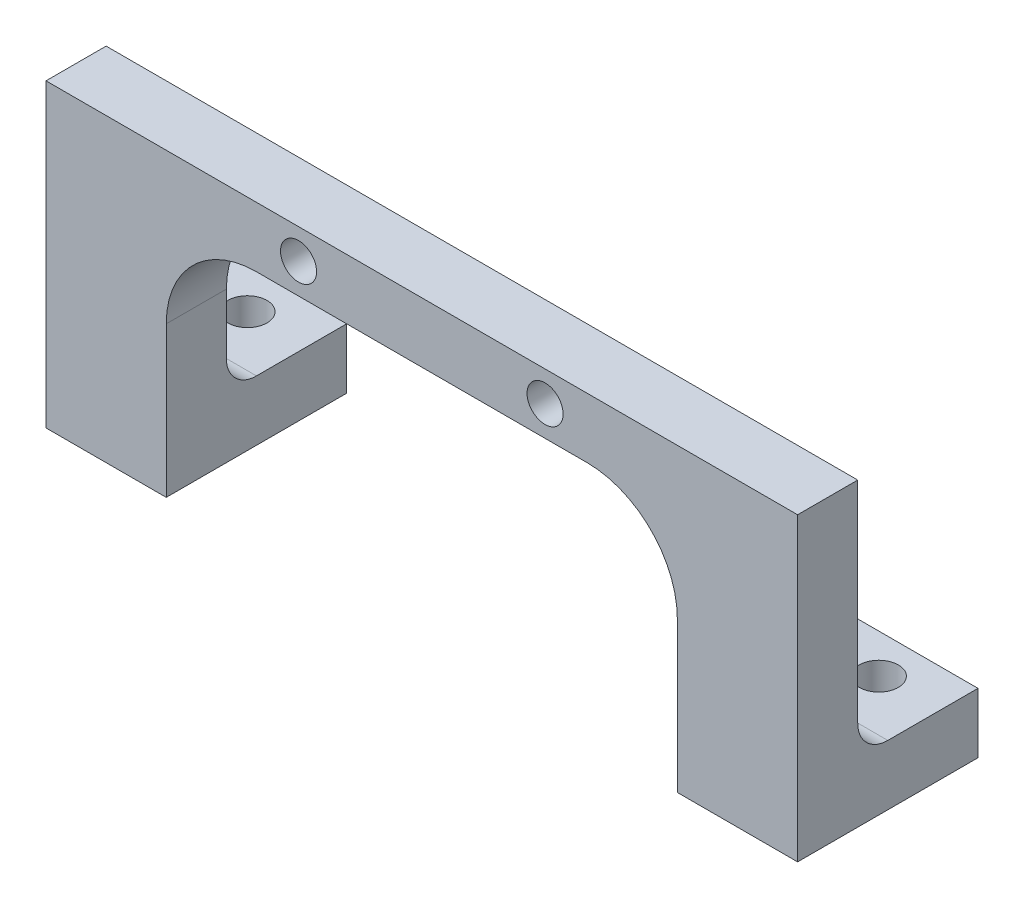
SolidWorks part; units mm, degrees
ref_plane "Front Plane" through (0, 0, 0) normal (0, 0, 1) x (1, 0, 0)
ref_plane "Top Plane" through (0, 0, 0) normal (0, 1, 0) x (1, 0, 0)
ref_plane "Right Plane" through (0, 0, 0) normal (1, 0, 0) x (0, 0, -1)
sketch "Sketch1" plane through (0, 0, 0) normal (1, 0, 0) x (0, 0, -1)
  line L1 (-0.3503, 12.7) -> (4.7297, 12.7)
  line L2 (-0.3503, 12.7) -> (-0.3503, -12.7)
  line L4 (4.7297, 12.7) -> (4.7297, -5.08)
  line L5 (-0.3503, 12.7) -> (0.9197, 6.35) construction
  line L7 (-0.3503, -12.7) -> (14.8897, -12.7)
  line L8 (-0.3503, -12.7) -> (-0.3503, -7.62)
  line L10 (14.8897, -12.7) -> (14.8897, -7.62)
  line L12 (-0.3503, -10.16) -> (-0.0963, -10.16) construction
  line L13 (0.9197, 6.35) -> (4.7297, 12.7) construction
  line L14 (7.2697, -7.62) -> (14.8897, -7.62)
  line L15 (4.7297, -10.16) -> (14.8897, -10.16) construction
  arc A0 (7.2697, -7.62) -> (4.7297, -5.08) centre (7.2697, -5.08) cw
  point P0 (0.9197, 6.35)
  point P280 (4.7297, -10.16)
  dimension "D5" = 2.54
  dimension "D1" = 5.08
  dimension "D2" = 5.08
  dimension "D3" = 25.4
  dimension "D4" = 15.24
extrude "Boss-Extrude1" add sketch "Sketch1" along normal blind 63.5 contours L14 A0 L4 L1 L2 L7 L10
sketch "Sketch2" plane through (0, 0, 0.3503) normal (0, 0, 1) x (1, 0, 0)
  line L0 (31.75, 12.7) -> (31.75, 0) construction
  line L1 (63.5, 12.7) -> (0, 12.7) construction
  line L2 (10.16, 0) -> (10.16, -12.7)
  line L3 (63.5, -12.7) -> (0, -12.7) construction
  line L6 (17.78, 7.62) -> (45.72, 7.62)
  line L8 (53.34, 0) -> (53.34, -12.7)
  line L9 (10.16, -12.7) -> (53.34, -12.7)
  line L12 (31.75, 15.24) -> (31.75, 0) construction
  line L13 (0, 12.7) -> (0, -12.7) construction
  arc A0 (17.78, 7.62) -> (10.16, 0) centre (17.78, 0) ccw
  arc A1 (53.34, 0) -> (45.72, 7.62) centre (45.72, 0) ccw
  circle A2 centre (21.336, 10.16) radius 1.524
  circle A3 centre (42.164, 10.16) radius 1.524
  point P23 (31.75, 7.62)
  dimension "D3" = 7.62
  dimension "D4" = 7.62
  dimension "D1" = 3.048
  dimension "D5" = 20.828
  dimension "D6" = 10.414
  dimension "D7" = 2.54
  dimension "D2" = 5.08
  dimension "D8" = 10.16
extrude "Cut-Extrude1" cut sketch "Sketch2" against normal through all
sketch "Sketch3" plane through (0, -7.62, 0) normal (0, 1, 0) x (1, 0, 0)
  line L2 (10.16, 14.8897) -> (0, 14.8897) construction
  line L4 (63.5, 14.8897) -> (53.34, 14.8897) construction
  line L5 (0, 7.2697) -> (0, 14.8897) construction
  line L6 (63.5, 7.2697) -> (63.5, 14.8897) construction
  circle A0 centre (5.08, 11.5877) radius 1.651
  circle A1 centre (58.42, 11.5877) radius 1.651
  dimension "D1" = 3.302
  dimension "D2" = 3.302
  dimension "D3" = 5.08
  dimension "D4" = 3.302
  dimension "D5" = 5.08
  dimension "D6" = 3.302
extrude "Cut-Extrude2" cut sketch "Sketch3" against normal through all
sketch "Sketch5" plane through (0, 0, 0.3503) normal (0, 0, 1) x (1, 0, 0)
  line L0 (31.75, 12.7) -> (31.75, 7.62)
  line L1 (63.5, 12.7) -> (0, 12.7) construction
  line L2 (45.72, 7.62) -> (17.78, 7.62) construction
